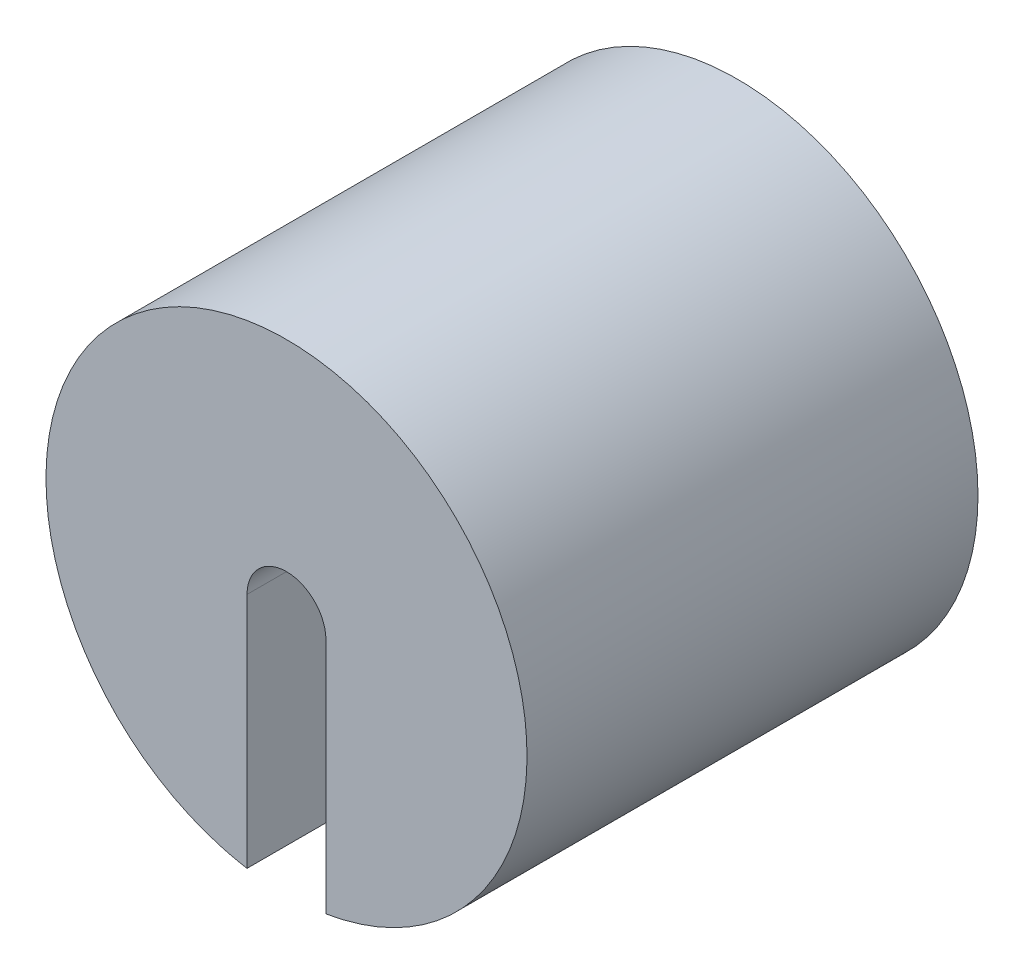
SolidWorks part; units mm, degrees
ref_plane "Plan de face" through (0, 0, 0) normal (0, 0, 1) x (1, 0, 0)
ref_plane "Plan de dessus" through (0, 0, 0) normal (0, 1, 0) x (1, 0, 0)
ref_plane "Plan de droite" through (0, 0, 0) normal (1, 0, 0) x (0, 0, -1)
sketch "Esquisse1" plane through (0, 0, 0) normal (0, 0, 1) x (1, 0, 0)
  line L0 (0, 16) -> (32, 16) construction
  line L6 (16, 32) -> (16, 0) construction
  circle A0 centre (16, 16) radius 12
  circle A1 centre (16, 16) radius 16
  dimension "D3" = 24
  dimension "D4" = 32
  dimension "D2" = 16
  dimension "D1" = 16
extrude "Boss.-Extru.1" add sketch "Esquisse1" along normal blind 30
sketch "Esquisse2" plane through (0, 0, 0) normal (1, 0, 0) x (0, 0, -1)
  line L1 (-30, 0) -> (-11, 0)
  line L2 (-30, 0) -> (-30, 32)
  line L3 (-30, 32) -> (-11, 32)
  line L4 (-11, 0) -> (-11, 32)
  line L6 (0, 0) -> (0, 32) construction
  line L7 (-30, 32) -> (0, 32) construction
  dimension "D1" = 11
  dimension "D2" = 32
  dimension "D3" = 19
  dimension "D4" = 0
sketch "Esquisse7" plane through (0, 0, 0) normal (0, 0, 1) x (1, 0, 0)
  circle A0 centre (16, 16) radius 16
extrude "Boss.-Extru.3" add sketch "Esquisse7" along normal blind 19 from offset 11
sketch "Esquisse4" plane through (0, 0, 0) normal (0, 1, 0) x (1, 0, 0)
  line L0 (32, -30) -> (32, 0) construction
  line L4 (0, -11) -> (32, -11) construction
  line L5 (11.75, -14.75) -> (20.25, -14.75)
  line L6 (11.75, -14.75) -> (11.75, -23.25)
  line L7 (11.75, -23.25) -> (20.25, -23.25)
  line L8 (20.25, -14.75) -> (20.25, -23.25)
  line L10 (28, 0) -> (4, 0) construction
  line L15 (16, 0) -> (16, -30) construction
  point P0 (0, 0)
  dimension "D1" = 16
  dimension "D2" = 8.5
  dimension "D3" = 11
  dimension "D4" = 8.5
  dimension "D5" = 4.25
  dimension "D6" = 3.75
extrude "Enlèv. mat.-Extru.1" cut sketch "Esquisse4" along normal blind 21
sketch "Esquisse6" plane through (0, 0, 0) normal (0, 1, 0) x (1, 0, 0)
  line L1 (13.375, -23.25) -> (18.625, -23.25)
  line L2 (13.375, -23.25) -> (13.375, -32.4387)
  line L3 (13.375, -32.4387) -> (18.625, -32.4387)
  line L4 (18.625, -23.25) -> (18.625, -32.4387)
  line L6 (16, 0) -> (16, -33.1421) construction
  line L8 (0, -30) -> (0, 0) construction
  dimension "D1" = 5.25
  dimension "D2" = 5.25
  dimension "D3" = 9.1887
  dimension "D4" = 16
extrude "Enlèv. mat.-Extru.3" cut sketch "Esquisse6" along normal blind 16
ref_plane "Plan2" through (0, 0, 30) normal (0, 0, 1) x (1, 0, 0)
sketch "Esquisse9" plane through (0, 0, 30) normal (0, 0, 1) x (1, 0, 0)
  line L0 (18.625, 16) -> (13.375, 16) construction
  circle A0 centre (16, 16) radius 2.625
  dimension "D1" = 5.25
extrude "Enlèv. mat.-Extru.4" cut sketch "Esquisse9" against normal blind 19
